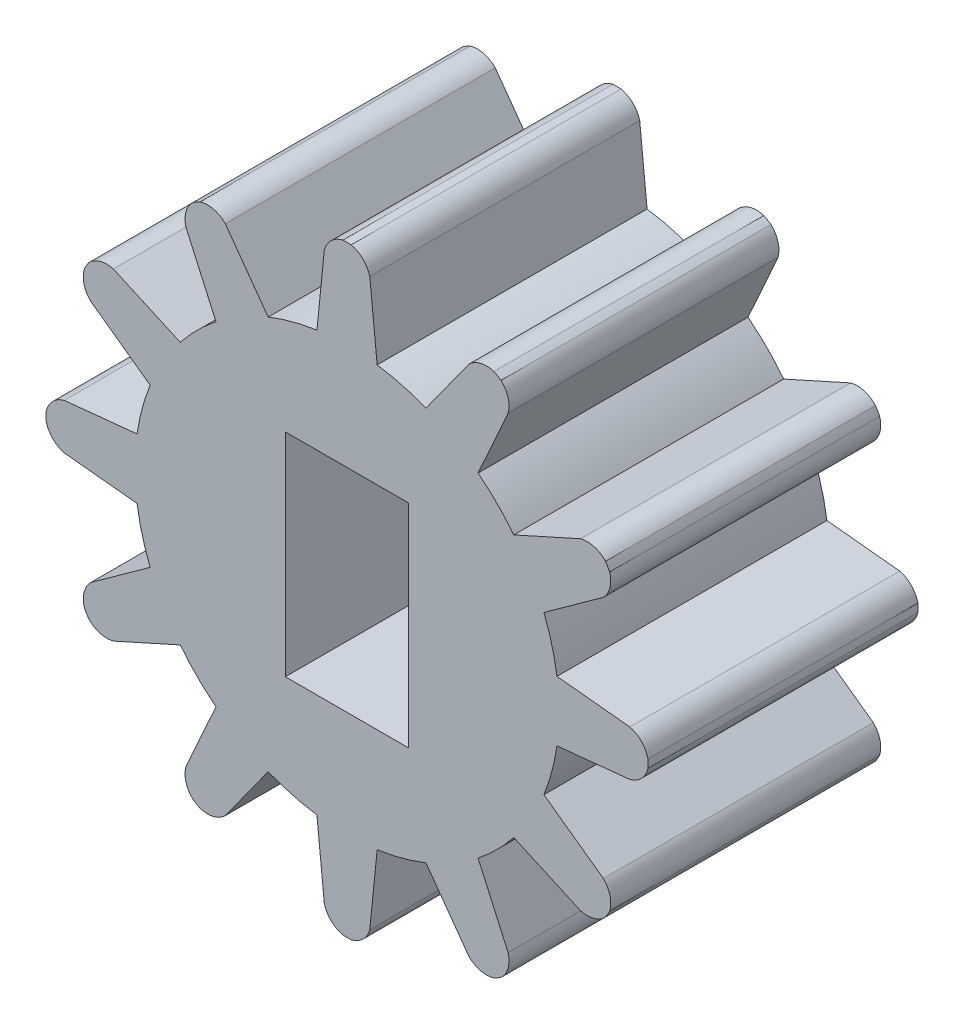
SolidWorks part; units mm, degrees
ref_plane "Front Plane" through (0, 0, 0) normal (0, 0, 1) x (1, 0, 0)
ref_plane "Top Plane" through (0, 0, 0) normal (0, 1, 0) x (1, 0, 0)
ref_plane "Right Plane" through (0, 0, 0) normal (1, 0, 0) x (0, 0, -1)
ref_plane "Plane1" through (0, 0, 20) normal (0, 0, 1) x (1, 0, 0)
ref_plane "Plane2" through (0, 0, 28.5) normal (0, 0, 1) x (1, 0, 0)
sketch "Sketch1" plane through (0, 0, 20) normal (0, 0, 1) x (1, 0, 0)
  circle A1 centre (0, 20.9252) radius 5.5
  dimension "D1" = 11
sketch "Sketch3" plane through (0, 0, 28.5) normal (0, 0, 1) x (1, 0, 0)
  line L0 (-3.9726, 20.9252) -> (15.3734, 20.9252) construction
  line L1 (0, 24.8978) -> (0, 8.7425) construction
  line L3 (-1.6, 23.6752) -> (1.6, 23.6752)
  line L4 (-1.6, 23.6752) -> (-1.6, 18.1752)
  line L5 (-1.6, 18.1752) -> (1.6, 18.1752)
  line L6 (1.6, 23.6752) -> (1.6, 18.1752)
  dimension "D1" = 3.2
  dimension "D2" = 5.5
  dimension "D3" = 1.6
  dimension "D4" = 2.75
extrude "Boss-Extrude2" add sketch "Sketch1" along normal blind 7
extrude "Cut-Extrude1" cut sketch "Sketch3" against normal blind 6
sketch "Sketch4" plane through (0, 0, 20) normal (0, 0, 1) x (1, 0, 0)
  line L0 (-0.5896, 28.2599) -> (-0.7807, 26.3695)
  line L1 (0, 28.7311) -> (0, 27.9031) construction
  line L2 (0.5896, 28.2599) -> (0.7807, 26.3695)
  line L3 (4.178, 26.9824) -> (3.3983, 25.2498)
  line L4 (3.1567, 27.5721) -> (2.046, 26.0305)
  line L5 (6.6468, 24.0819) -> (5.1053, 22.9713)
  line L6 (6.0572, 25.1032) -> (4.3246, 24.3235)
  line L7 (7.3347, 20.3356) -> (5.4443, 20.1445)
  line L8 (7.3347, 21.5149) -> (5.4443, 21.7059)
  line L9 (6.0572, 16.7473) -> (4.3246, 17.527)
  line L10 (6.6468, 17.7685) -> (5.1053, 18.8792)
  line L11 (3.1567, 14.2784) -> (2.046, 15.82)
  line L12 (4.178, 14.868) -> (3.3983, 16.6007)
  line L13 (-0.5896, 13.5906) -> (-0.7807, 15.4809)
  line L14 (0.5896, 13.5906) -> (0.7807, 15.4809)
  line L15 (-4.178, 14.868) -> (-3.3983, 16.6007)
  line L16 (-3.1567, 14.2784) -> (-2.046, 15.82)
  line L17 (-6.6468, 17.7685) -> (-5.1053, 18.8792)
  line L18 (-6.0572, 16.7473) -> (-4.3246, 17.527)
  line L19 (-7.3347, 21.5149) -> (-5.4443, 21.7059)
  line L20 (-7.3347, 20.3356) -> (-5.4443, 20.1445)
  line L21 (-6.0572, 25.1032) -> (-4.3246, 24.3235)
  line L22 (-6.6468, 24.0819) -> (-5.1053, 22.9713)
  line L23 (-3.1567, 27.5721) -> (-2.046, 26.0305)
  line L24 (-4.178, 26.9824) -> (-3.3983, 25.2498)
  circle A0 centre (0, 20.9252) radius 5.5 construction
  arc A1 (-0.5896, 28.2599) -> (-0.1067, 28.7283) centre (0.0391, 28.0948) cw
  arc A2 (-0.1067, 28.7283) -> (0.1067, 28.7283) centre (0, 26.7184) cw
  arc A3 (0.5896, 28.2599) -> (0.1067, 28.7283) centre (-0.0391, 28.0948) ccw
  arc A4 (-0.7807, 26.3695) -> (0.7807, 26.3695) centre (0, 20.9252) cw
  arc A5 (2.046, 26.0305) -> (3.3983, 25.2498) centre (0, 20.9252) cw
  arc A6 (4.178, 26.9824) -> (3.9939, 27.6295) centre (3.551, 27.1538) ccw
  arc A7 (3.8091, 27.7362) -> (3.9939, 27.6295) centre (2.8966, 25.9422) cw
  arc A8 (3.1567, 27.5721) -> (3.8091, 27.7362) centre (3.6186, 27.1147) cw
  arc A9 (4.3246, 24.3235) -> (5.1053, 22.9713) centre (0, 20.9252) cw
  arc A10 (6.6468, 24.0819) -> (6.811, 24.7344) centre (6.1895, 24.5438) ccw
  arc A11 (6.7043, 24.9191) -> (6.811, 24.7344) centre (5.017, 23.8218) cw
  arc A12 (6.0572, 25.1032) -> (6.7043, 24.9191) centre (6.2286, 24.4762) cw
  arc A13 (5.4443, 21.7059) -> (5.4443, 20.1445) centre (0, 20.9252) cw
  arc A14 (7.3347, 20.3356) -> (7.803, 20.8186) centre (7.1696, 20.9643) ccw
  arc A15 (7.803, 21.0319) -> (7.803, 20.8186) centre (5.7931, 20.9252) cw
  arc A16 (7.3347, 21.5149) -> (7.803, 21.0319) centre (7.1696, 20.8862) cw
  arc A17 (5.1053, 18.8792) -> (4.3246, 17.527) centre (0, 20.9252) cw
  arc A18 (6.0572, 16.7473) -> (6.7043, 16.9313) centre (6.2286, 17.3743) ccw
  arc A19 (6.811, 17.1161) -> (6.7043, 16.9313) centre (5.017, 18.0287) cw
  arc A20 (6.6468, 17.7685) -> (6.811, 17.1161) centre (6.1895, 17.3066) cw
  arc A21 (3.3983, 16.6007) -> (2.046, 15.82) centre (0, 20.9252) cw
  arc A22 (3.1567, 14.2784) -> (3.8091, 14.1143) centre (3.6186, 14.7357) ccw
  arc A23 (3.9939, 14.221) -> (3.8091, 14.1143) centre (2.8966, 15.9082) cw
  arc A24 (4.178, 14.868) -> (3.9939, 14.221) centre (3.551, 14.6967) cw
  arc A25 (0.7807, 15.4809) -> (-0.7807, 15.4809) centre (0, 20.9252) cw
  arc A26 (-0.5896, 13.5906) -> (-0.1067, 13.1222) centre (0.0391, 13.7557) ccw
  arc A27 (0.1067, 13.1222) -> (-0.1067, 13.1222) centre (0, 15.1321) cw
  arc A28 (0.5896, 13.5906) -> (0.1067, 13.1222) centre (-0.0391, 13.7557) cw
  arc A29 (-2.046, 15.82) -> (-3.3983, 16.6007) centre (0, 20.9252) cw
  arc A30 (-4.178, 14.868) -> (-3.9939, 14.221) centre (-3.551, 14.6967) ccw
  arc A31 (-3.8091, 14.1143) -> (-3.9939, 14.221) centre (-2.8966, 15.9082) cw
  arc A32 (-3.1567, 14.2784) -> (-3.8091, 14.1143) centre (-3.6186, 14.7357) cw
  arc A33 (-4.3246, 17.527) -> (-5.1053, 18.8792) centre (0, 20.9252) cw
  arc A34 (-6.6468, 17.7685) -> (-6.811, 17.1161) centre (-6.1895, 17.3066) ccw
  arc A35 (-6.7043, 16.9313) -> (-6.811, 17.1161) centre (-5.017, 18.0287) cw
  arc A36 (-6.0572, 16.7473) -> (-6.7043, 16.9313) centre (-6.2286, 17.3743) cw
  arc A37 (-5.4443, 20.1445) -> (-5.4443, 21.7059) centre (0, 20.9252) cw
  arc A38 (-7.3347, 21.5149) -> (-7.803, 21.0319) centre (-7.1696, 20.8862) ccw
  arc A39 (-7.803, 20.8186) -> (-7.803, 21.0319) centre (-5.7931, 20.9252) cw
  arc A40 (-7.3347, 20.3356) -> (-7.803, 20.8186) centre (-7.1696, 20.9643) cw
  arc A41 (-5.1053, 22.9713) -> (-4.3246, 24.3235) centre (0, 20.9252) cw
  arc A42 (-6.0572, 25.1032) -> (-6.7043, 24.9191) centre (-6.2286, 24.4762) ccw
  arc A43 (-6.811, 24.7344) -> (-6.7043, 24.9191) centre (-5.017, 23.8218) cw
  arc A44 (-6.6468, 24.0819) -> (-6.811, 24.7344) centre (-6.1895, 24.5438) cw
  arc A45 (-3.3983, 25.2498) -> (-2.046, 26.0305) centre (0, 20.9252) cw
  arc A46 (-3.1567, 27.5721) -> (-3.8091, 27.7362) centre (-3.6186, 27.1147) ccw
  arc A47 (-3.9939, 27.6295) -> (-3.8091, 27.7362) centre (-2.8966, 25.9422) cw
  arc A48 (-4.178, 26.9824) -> (-3.9939, 27.6295) centre (-3.551, 27.1538) cw
  circle A49 centre (0, 20.9252) radius 5.5 construction
  point P97 (0, 20.9252)
  dimension "D1" = 12
  dimension "D2" = 5.5
  dimension "D4" = 0.65
  dimension "D3" = 1.9
extrude "Boss-Extrude3" add sketch "Sketch4" along normal up to surface (7 mm away) up to face at (0, 20.9252, 27)
